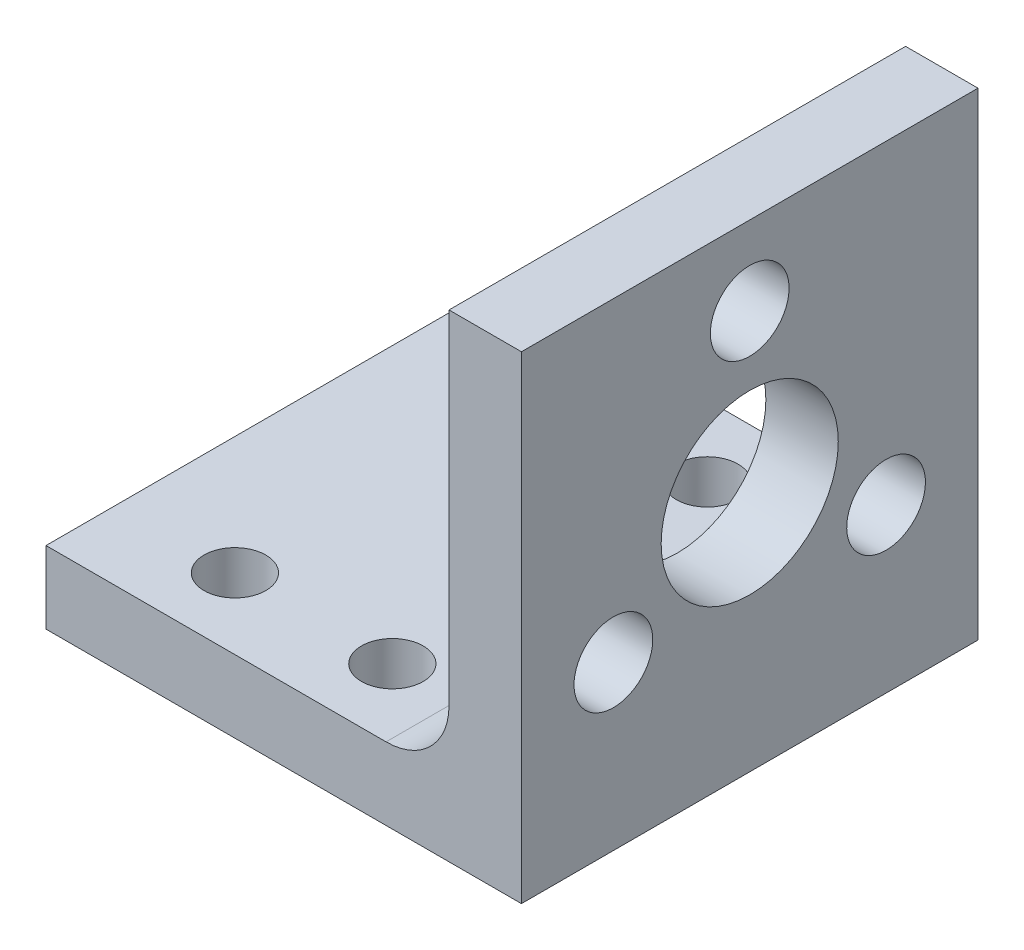
SolidWorks part; units mm, degrees
ref_plane "Front Plane" through (0, 0, 0) normal (0, 0, 1) x (1, 0, 0)
ref_plane "Top Plane" through (0, 0, 0) normal (0, 1, 0) x (1, 0, 0)
ref_plane "Right Plane" through (0, 0, 0) normal (1, 0, 0) x (0, 0, -1)
sketch "Sketch1" plane through (0, 0, 0) normal (0, 0, 1) x (1, 0, 0)
  line L0 (0, 38.5572) -> (0, 0)
  line L1 (0, 0) -> (-38.354, 0)
  line L2 (-38.354, 0) -> (-38.354, 5.842)
  line L3 (-38.354, 5.842) -> (-10.922, 5.842)
  line L4 (-5.842, 10.922) -> (-5.842, 38.5572)
  line L5 (-5.842, 38.5572) -> (0, 38.5572)
  arc A0 (-10.922, 5.842) -> (-5.842, 10.922) centre (-10.922, 10.922) ccw
  dimension "D5" = 5.08
  dimension "D1" = 38.354
  dimension "D2" = 38.5572
  dimension "D3" = 5.842
  dimension "D4" = 5.842
extrude "Boss-Extrude1" add sketch "Sketch1" along normal blind 36.83
sketch "Sketch2" plane through (0, 0, 0) normal (1, 0, 0) x (0, 0, -1)
  line L0 (-36.83, 38.5572) -> (0, 38.5572) construction
  circle A0 centre (-18.415, 19.5072) radius 7.1438
  circle A1 centre (-18.415, 32.2072) radius 3.175
  circle A2 centre (-7.4165, 13.1572) radius 3.175
  circle A3 centre (-29.4135, 13.1572) radius 3.175
  point P6 (-18.415, 38.5572)
  dimension "D2" = 14.2875
  dimension "D4" = 6.35
  dimension "D1" = 19.05
  dimension "D3" = 12.7
  dimension "D5" = 0
  dimension "D6" = 3
extrude "Cut-Extrude1" cut sketch "Sketch2" against normal through all
sketch "Sketch3" plane through (0, 0, 0) normal (0, -1, 0) x (1, 0, 0)
  line L0 (-38.354, 18.415) -> (-2.3466, 18.415) construction
  line L1 (-38.354, 36.83) -> (-38.354, 0) construction
  circle A0 centre (-28.829, 31.115) radius 2.4892
  circle A1 centre (-16.129, 31.115) radius 2.4892
  circle A2 centre (-16.129, 5.715) radius 2.4892
  circle A3 centre (-28.829, 5.715) radius 2.4892
  dimension "D1" = 4.9784
  dimension "D2" = 9.525
  dimension "D3" = 12.7
  dimension "D4" = 25.4
extrude "Cut-Extrude2" cut sketch "Sketch3" against normal through all
